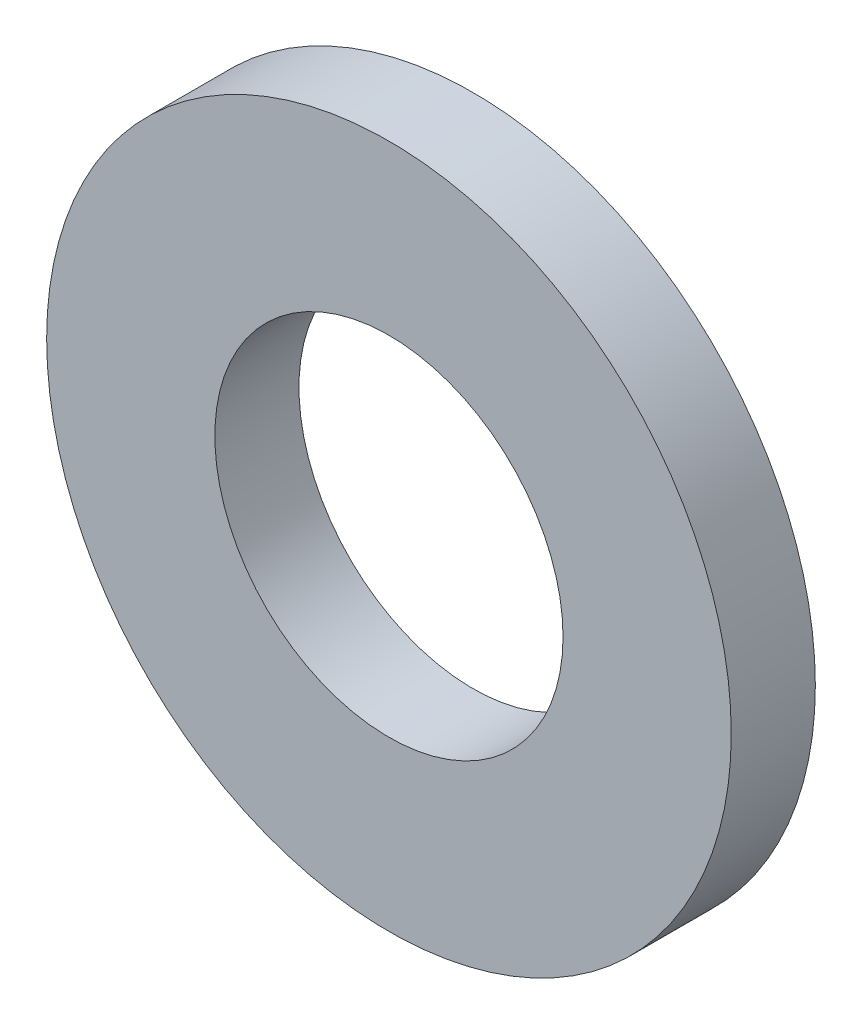
SolidWorks part; units mm, degrees
ref_plane "Plan de face" through (0, 0, 0) normal (0, 0, 1) x (1, 0, 0)
ref_plane "Plan de dessus" through (0, 0, 0) normal (0, 1, 0) x (1, 0, 0)
ref_plane "Plan de droite" through (0, 0, 0) normal (1, 0, 0) x (0, 0, -1)
sketch "Esquisse1" plane through (0, 0, 0) normal (0, 0, 1) x (1, 0, 0)
  circle A0 centre (0, 0) radius 10.35
  circle A1 centre (0, 0) radius 20.35
  dimension "D1" = 20.7
  dimension "D2" = 10
extrude "Boss.-Extru.1" add sketch "Esquisse1" along normal blind 5
